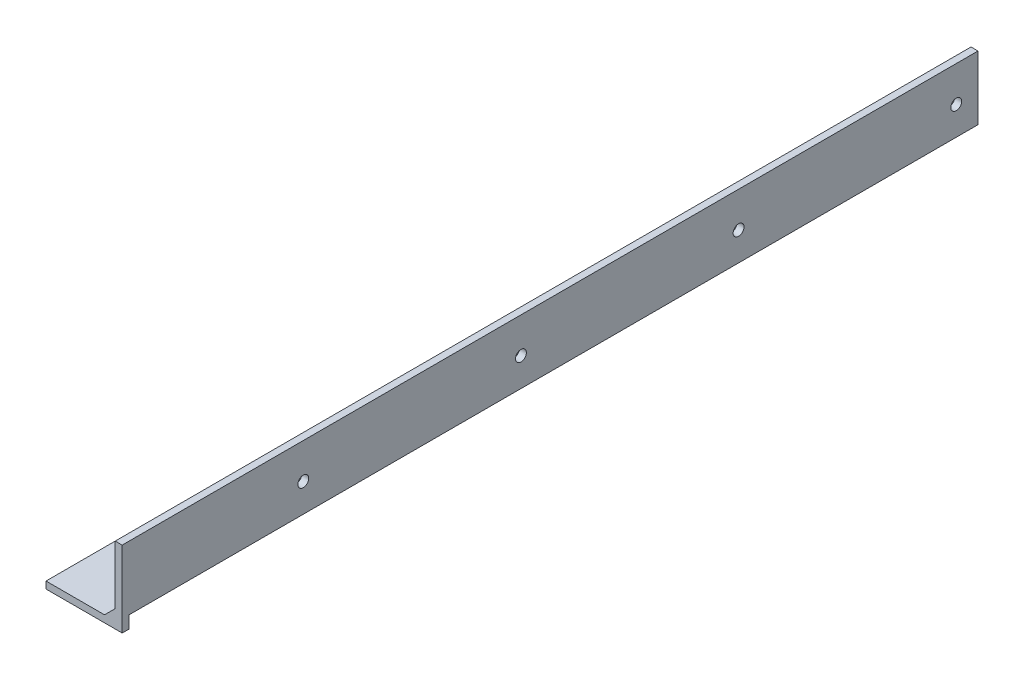
SolidWorks part; units mm, degrees
material "ABS"
ref_plane "Front Plane" through (0, 0, 0) normal (0, 0, 1) x (1, 0, 0)
ref_plane "Top Plane" through (0, 0, 0) normal (0, 1, 0) x (1, 0, 0)
ref_plane "Right Plane" through (0, 0, 0) normal (1, 0, 0) x (0, 0, -1)
sketch "Sketch1" plane through (0, 0, 0) normal (0, 0, 1) x (1, 0, 0)
  line L0 (0, 3.5921) -> (-3.5921, 0)
  line L1 (-3.5921, 0) -> (-22.225, 0)
  line L2 (-22.225, 0) -> (-22.225, 2.032)
  line L3 (-22.225, 2.032) -> (-5.1522, 2.032)
  line L4 (-5.1522, 2.032) -> (-2.032, 5.1522)
  line L5 (-2.032, 5.1522) -> (-2.032, 22.225)
  line L6 (-2.032, 22.225) -> (0, 22.225)
  line L7 (0, 22.225) -> (0, 3.5921)
  dimension "D1" = 2.032
  dimension "D2" = 22.225
  dimension "D3" = 22.225
  dimension "D4" = 45
  dimension "D5" = 5.08
  dimension "D6" = 2.54
extrude "Boss-Extrude1" add sketch "Sketch1" along normal blind 247.65
hole_wizard "1/8 (0.1250) Dowel Hole1" positions "Sketch2" profile "Sketch3" hole size "1/8" standard "ANSI Inch" end condition through all
sketch "Sketch2" plane through (-2.032, 0, 0) normal (-1, 0, 0) x (0, 0, 1)
  line L0 (247.65, 22.225) -> (247.65, 5.1522) construction
  line L2 (247.65, 0) -> (0, 0) construction
  point P0 (196.85, 11.9062)
  point P2 (69.85, 11.9062)
  point P4 (133.35, 11.9062)
  point P6 (6.35, 11.9062)
  dimension "D1" = 50.8
  dimension "D2" = 63.5
  dimension "D3" = 63.5
  dimension "D4" = 63.5
  dimension "D5" = 11.9062
sketch "Sketch3" plane through (-2.032, 11.9062, 196.85) normal (0, 1, 0) x (0, 0, 1)
  line L0 (0, 0) -> (0, 2.032)
  line L1 (0, 2.032) -> (1.5875, 2.032)
  line L2 (1.5875, 2.032) -> (1.5875, 0)
  line L5 (1.5875, 0) -> (0, 0)
  line L11 (0, -6.35) -> (0, 107.95) construction
  dimension "Thru Hole Dia." = 3.175
  dimension "Thru Hole Depth" = 2.032
hole_wizard "1/8 (0.1250) Dowel Hole2" positions "Sketch4" profile "Sketch5" hole size "1/8" standard "ANSI Inch" end condition through all
sketch "Sketch4" plane through (0, 2.032, 0) normal (0, 1, 0) x (1, 0, 0)
  line L0 (-5.1522, -247.65) -> (-22.225, -247.65) construction
  line L1 (0, -247.65) -> (0, 0) construction
  point P0 (-11.9062, -225.425)
  point P2 (-11.9062, -48.8188)
  dimension "D1" = 22.225
  dimension "D2" = 198.8312
  dimension "D3" = 11.9062
sketch "Sketch5" plane through (-11.9062, 2.032, 225.425) normal (1, 0, 0) x (0, 0, 1)
  line L0 (0, 0) -> (0, 2.032)
  line L1 (0, 2.032) -> (1.5875, 2.032)
  line L2 (1.5875, 2.032) -> (1.5875, 0)
  line L5 (1.5875, 0) -> (0, 0)
  line L11 (0, -6.35) -> (0, 107.95) construction
  dimension "Thru Hole Dia." = 3.175
  dimension "Thru Hole Depth" = 2.032
sketch "Sketch6" plane through (0, 0, 247.65) normal (0, 0, 1) x (1, 0, 0)
  line L0 (-22.225, 0) -> (0, 0)
  line L1 (-22.225, 2.032) -> (-22.225, 0)
  line L2 (-22.225, 2.032) -> (-5.1522, 2.032)
  line L3 (0, 22.225) -> (0, 0)
  line L4 (-5.1522, 2.032) -> (-2.032, 5.1522)
  line L5 (-2.032, 5.1522) -> (-2.032, 22.225)
  line L6 (0, 22.225) -> (-2.032, 22.225) construction
  line L7 (-2.032, 22.225) -> (0, 22.225)
extrude "Boss-Extrude2" add sketch "Sketch6" along normal blind 2.032
sketch "Sketch7" plane through (-2.032, 0, 0) normal (-1, 0, 0) x (0, 0, 1)
  text T0 "AFT" font "Arial" height 7.62
extrude "Cut-Extrude1" cut sketch "Sketch7" against normal blind 0.254
sketch "Sketch10" plane through (0, 2.032, 0) normal (0, 1, 0) x (1, 0, 0)
  text T0 "DRILL HOLES .281" font "Arial" height 6.35
extrude "Cut-Extrude2" cut sketch "Sketch10" against normal blind 0.254
